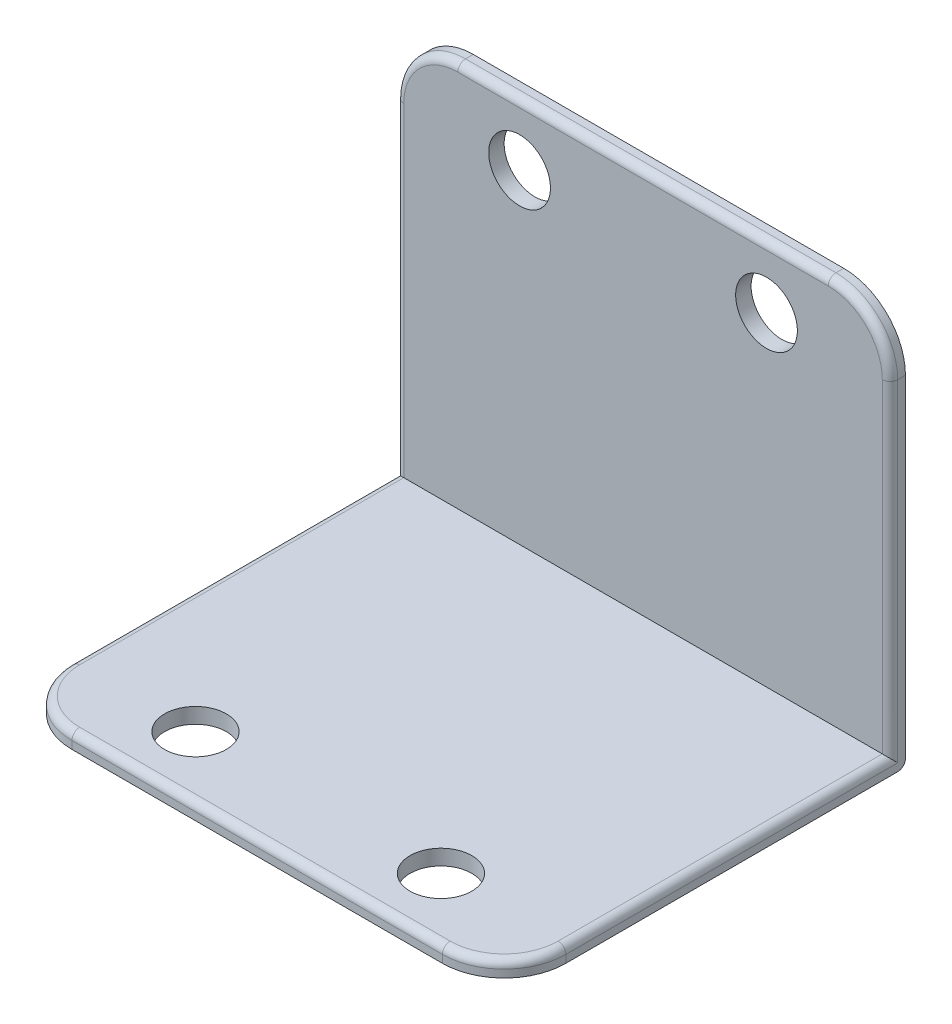
SolidWorks part; units mm, degrees
ref_plane "Front Plane" through (0, 0, 0) normal (0, 0, 1) x (1, 0, 0)
ref_plane "Top Plane" through (0, 0, 0) normal (0, 1, 0) x (1, 0, 0)
ref_plane "Right Plane" through (0, 0, 0) normal (1, 0, 0) x (0, 0, -1)
sketch "Sketch1" plane through (0, 0, 0) normal (0, 1, 0) x (1, 0, 0)
  line L0 (-16, 0) -> (0, 0) construction
  line L1 (-16, -13) -> (16, -13)
  line L2 (-16, -13) -> (-16, 13)
  line L3 (-16, 13) -> (16, 13)
  line L4 (16, -13) -> (16, 13)
  line L5 (-16, -13) -> (16, 13) construction
  line L6 (-16, 13) -> (16, -13) construction
  line L7 (0, 0) -> (16, 0) construction
  line L8 (16, 0) -> (8, 0) construction
  line L9 (-16, 0) -> (-8, 0) construction
  line L10 (-16, -9) -> (16, -9) construction
  circle A0 centre (-8, -9) radius 2
  circle A1 centre (7.9053, -9) radius 2
  point P0 (0, 0)
  dimension "D4" = 4
  dimension "D5" = 4
  dimension "D1" = 26
  dimension "D2" = 32
  dimension "D3" = 4
extrude "Boss-Extrude1" add sketch "Sketch1" along normal blind 1
fillet "Fillet1" radius 4 1 edges at (-16, 0.5, 13)
fillet "Fillet2" radius 4 1 edges at (16, 0.5, 13)
sketch "Sketch2" plane through (0, 1, 0) normal (0, 1, 0) x (1, 0, 0)
  line L0 (16, -9) -> (16, 13) construction
  line L1 (-16, 13) -> (16, 13)
  line L2 (-16, 13) -> (-16, 12)
  line L3 (-16, 12) -> (16, 12)
  line L4 (16, 13) -> (16, 12)
  line L5 (-16, 13) -> (16, 12) construction
  line L6 (-16, 12) -> (16, 13) construction
  point P4 (0, 12.5)
  dimension "D1" = 1
extrude "Boss-Extrude2" add sketch "Sketch2" along normal blind 25
fillet "Fillet3" radius 4 1 edges at (16, 26, -12.5)
fillet "Fillet4" radius 4 1 edges at (-16, 26, -12.5)
sketch "Sketch3" plane through (0, 0, -12) normal (0, 0, 1) x (1, 0, 0)
  line L0 (-16, 22) -> (16, 22) construction
  line L1 (-16, 22) -> (-16, 1) construction
  line L2 (16, 22) -> (16, 1) construction
  line L3 (-12, 26) -> (12, 26) construction
  circle A0 centre (-8, 22) radius 2
  circle A1 centre (8, 22) radius 2
  dimension "D3" = 8
  dimension "D4" = 4
  dimension "D5" = 4
  dimension "D1" = 4
  dimension "D2" = 8
extrude "Cut-Extrude1" cut sketch "Sketch3" against normal through all
fillet "Fillet5" radius 0.5 5 edges at (-16, 11.5, -12) (-14.8284, 24.8284, -12) (0, 26, -12) (14.8284, 24.8284, -12) (16, 11.5, -12)
fillet "Fillet6" radius 0.5 5 edges at (16, 1, -1.75) (14.8284, 1, 11.8284) (0, 1, 13) (-14.8284, 1, 11.8284) (-16, 1, -1.75)
fillet "Fillet7" radius 0.5 1 edges at (0, 0, -13)
